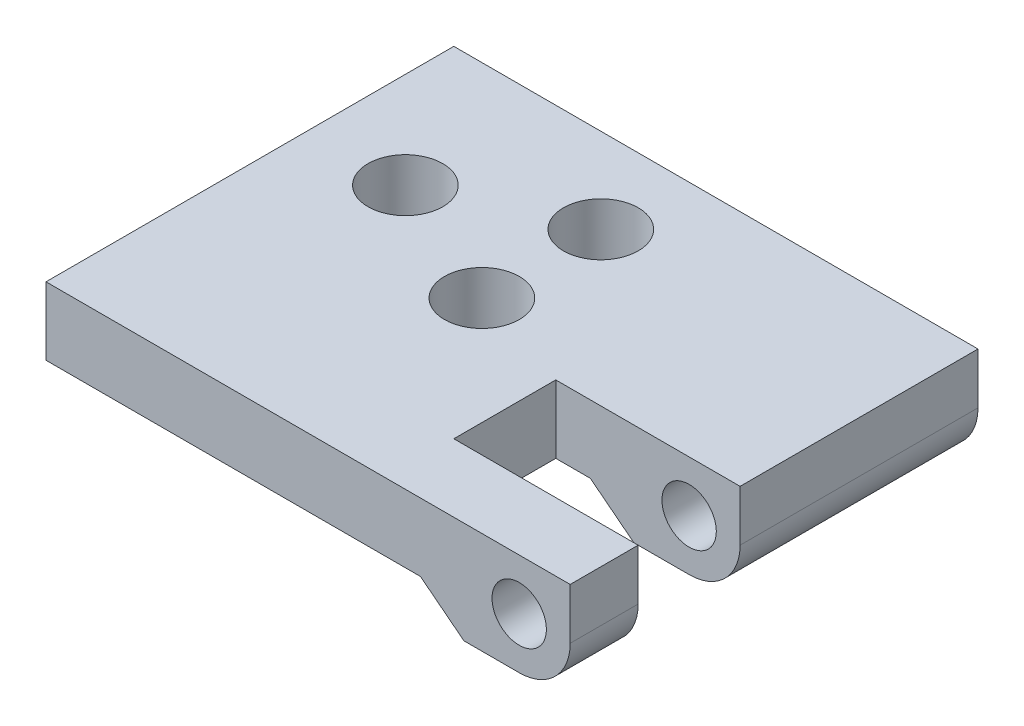
SolidWorks part; units mm, degrees
ref_plane "前视基准面" through (0, 0, 0) normal (0, 0, 1) x (1, 0, 0)
ref_plane "上视基准面" through (0, 0, 0) normal (0, 1, 0) x (1, 0, 0)
ref_plane "右视基准面" through (0, 0, 0) normal (1, 0, 0) x (0, 0, -1)
sketch "草图1" plane through (0, 0, 0) normal (0, 1, 0) x (1, 0, 0)
  line L0 (-12.0433, 4.7008) -> (-12.0433, -2.2992) construction
  line L1 (-25.6944, 9.7008) -> (4.3056, 9.7008)
  line L2 (-25.6944, 9.7008) -> (-25.6944, -14.2992)
  line L3 (-25.6944, -14.2992) -> (4.3056, -14.2992)
  line L4 (4.3056, 9.7008) -> (4.3056, -14.2992)
  line L5 (4.3056, -10.2992) -> (-5.6944, -10.2992)
  line L6 (4.3056, -10.2992) -> (4.3056, -4.2992)
  line L7 (4.3056, -4.2992) -> (-5.6944, -4.2992)
  line L8 (-5.6944, -10.2992) -> (-5.6944, -4.2992)
  circle A0 centre (-20.0433, 1.2008) radius 2.2
  circle A1 centre (-12.0433, 4.7008) radius 2.2
  circle A2 centre (-12.0433, -2.2992) radius 2.2
  point P10 (-12.0433, 1.2008)
  dimension "D7" = 8
  dimension "D8" = 7
  dimension "D1" = 20
  dimension "D2" = 20
  dimension "D3" = 6
  dimension "D4" = 10
  dimension "D5" = 4
  dimension "D6" = 8.5
extrude "凸台-拉伸2" add sketch "草图1" along normal blind 6
sketch "草图2" plane through (0, 0, 14.2992) normal (0, 0, 1) x (1, 0, 0)
  line L0 (4.3056, 0) -> (0, 6) construction
  line L1 (-25.6944, 6) -> (4.3056, 6) construction
  circle A0 centre (2.1528, 3) radius 1.6
  point P5 (2.1528, 3)
extrude "切除-拉伸2" cut sketch "草图2" against normal blind 26
sketch "草图3" plane through (0, 0, 0) normal (0, -1, 0) x (1, 0, 0)
  line L0 (-25.6944, -9.7008) -> (4.3056, -9.7008) construction
  line L1 (-25.6944, 14.2992) -> (-3.6581, 14.2992)
  line L2 (-25.6944, 14.2992) -> (-25.6944, -9.7008)
  line L3 (-25.6944, -9.7008) -> (-3.6581, -9.7008)
  line L4 (-3.6581, 14.2992) -> (-3.6581, -9.7008)
extrude "切除-拉伸3" cut sketch "草图3" against normal blind 2
sketch "草图4" plane through (0, 0, 14.2992) normal (0, 0, 1) x (1, 0, 0)
  line L0 (-3.6581, 2) -> (-1.1001, 0)
  line L1 (-1.1001, 0) -> (-3.6581, 0)
  line L2 (-3.6581, 0) -> (-3.6581, 2)
  line L3 (-1.1001, 0) -> (-0.8205, 0)
  line L4 (-3.6581, 0) -> (4.3056, 0) construction
  line M6 (-3.6581, 2) -> (-3.6581, 0)
  line M7 (-3.6581, 0) -> (4.3056, 0)
extrude "切除-拉伸4" cut sketch "草图4" against normal blind 27 contours L0 M6 M7
sketch "草图5" plane through (0, 0, -9.7008) normal (0, 0, -1) x (-1, 0, 0)
  line L0 (25.6944, 6) -> (-4.3056, 6) construction
  line L1 (-4.3056, 6) -> (-4.3056, 0) construction
  line L4 (-2.1528, 0) -> (-4.3056, 0)
  line L5 (-4.3056, 0) -> (-4.3056, 0.9106)
  circle A0 centre (-2.1528, 3) radius 3 construction
  arc A2 (-2.1528, 0) -> (-4.3056, 0.9106) centre (-2.1528, 3) cw
  point P16 (0, 0)
  point P17 (0, 0)
  point P18 (0, 0)
extrude "切除-拉伸7" cut sketch "草图5" against normal blind 24
sketch "草图8" plane through (0, 0, -9.7008) normal (0, 0, -1) x (-1, 0, 0)
  line L0 (-4.3056, 6) -> (-5.1528, 6)
  line L1 (-5.1528, 6) -> (-5.1528, 3)
  line L2 (-4.3056, 6) -> (-4.3056, 5.0894)
  line L3 (-4.3056, 6) -> (-4.3056, 0.9106) construction
  line L4 (-4.3056, 5.0894) -> (-4.3056, 0.9106)
  circle A1 centre (-2.1528, 3) radius 3 construction
  arc A2 (-4.3056, 0.9106) -> (-5.1528, 3) centre (-2.1528, 3) cw
  line M8 (-4.3056, 6) -> (-4.3056, 0.9106)
extrude "凸台-拉伸4" add sketch "草图8" against normal blind 24 contours A2 L0 L1 M8
sketch "草图9" plane through (4.3056, 0, 0) normal (-1, 0, 0) x (0, 0, 1)
  line L1 (10.2992, 6) -> (4.2992, 6)
  line L2 (10.2992, 6) -> (10.2992, 0.9106)
  line L3 (10.2992, 0.9106) -> (4.2992, 0.9106)
  line L4 (4.2992, 6) -> (4.2992, 0.9106)
extrude "切除-拉伸8" cut sketch "草图9" against normal blind 24
